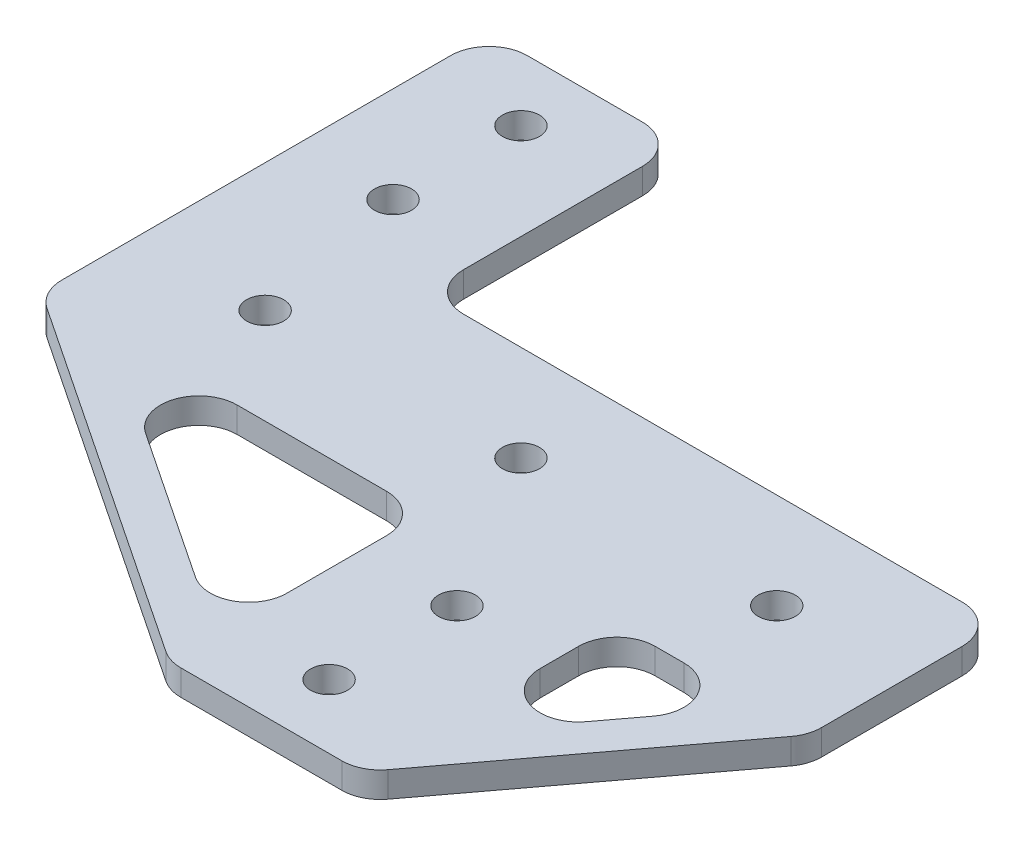
SolidWorks part; units mm, degrees
material "Thornel Mat VMA"
ref_plane "前视基准面" through (0, 0, 0) normal (0, 0, 1) x (1, 0, 0)
ref_plane "上视基准面" through (0, 0, 0) normal (0, 1, 0) x (1, 0, 0)
ref_plane "右视基准面" through (0, 0, 0) normal (1, 0, 0) x (0, 0, -1)
other "Configuration Table"
sketch "草图1" plane through (0, 0, 0) normal (0, 1, 0) x (1, 0, 0)
  line L0 (15, 35) -> (15, 15) construction
  line L1 (0, 0) -> (15, 0) construction
  line L2 (0, 0) -> (0, 35) construction
  line L3 (0, 35) -> (15, 35) construction
  line L4 (15, 0) -> (15, 35) construction
  line L5 (0, 0) -> (60, 0) construction
  line L6 (0, 0) -> (0, 15)
  line L7 (0, 15) -> (60, 15) construction
  line L8 (60, 0) -> (60, 15) construction
  line L9 (30, 15) -> (45, 15) construction
  line L10 (30, 15) -> (30, -20) construction
  line L11 (30, -20) -> (45, -20) construction
  line L12 (45, 15) -> (45, -20) construction
  line L13 (15, 15) -> (30, 15) construction
  line L14 (45, 15) -> (60, 15) construction
  line L15 (15, 0) -> (30, 0) construction
  line L16 (30, 0) -> (30, -20) construction
  line L17 (45, -20) -> (45, 0) construction
  line L18 (45, 0) -> (60, 0) construction
  line L19 (0, 0) -> (30, -20) construction
  line L20 (15, 35) -> (60, 15) construction
  line L21 (60, 0) -> (45, -20) construction
  line L22 (5.4083, 0) -> (30, 0)
  line L23 (30, 0) -> (30, -16.3944)
  line L24 (30, -16.3944) -> (5.4083, 0)
  line L25 (15, 28.8238) -> (15, 15) construction
  line L26 (15, 15) -> (52.6134, 15) construction
  line L28 (56.25, 0) -> (45, -15)
  line L29 (45, -15) -> (45, 0)
  line L30 (45, 0) -> (56.25, 0)
  line L31 (0, 0) -> (30, -20)
  line L32 (30, -20) -> (45, -20)
  line L33 (45, -20) -> (60, 0)
  line L34 (60, 0) -> (60, 15)
  line L35 (60, 15) -> (15, 35) construction
  line L36 (15, 35) -> (0, 35)
  line L37 (0, 35) -> (0, 0)
  line L38 (7.5, 46.7802) -> (7.5, -14.9998) construction
  line L39 (37.5, 36.5055) -> (37.5, -31.8877) construction
  line L40 (-7.4455, 7.5) -> (81.0629, 7.5) construction
  line L43 (26.7502, 15) -> (15, 15)
  line L44 (15, 15) -> (15, 28.8238)
  line L45 (45, 15) -> (60, 15)
  line L46 (15, 28.8238) -> (26.7502, 15)
  line L47 (15, 35) -> (32, 15)
  line L48 (32, 15) -> (45, 15)
  circle A1 centre (10, 7.5) radius 1.45
  circle A2 centre (30, 7.5) radius 1.45
  circle A3 centre (50, 7.5) radius 1.45
  circle A4 centre (7.5, 20) radius 1.45
  circle A5 centre (7.5, 30) radius 1.45
  circle A6 centre (37.5, -5) radius 1.45
  circle A7 centre (37.5, -15) radius 1.45
  dimension "D7" = 2.9
  dimension "D9" = 5
  dimension "D10" = 10
  dimension "D11" = 5
  dimension "D13" = 10
  dimension "D15" = 20
  dimension "D16" = 20
  dimension "D8" = 10
  dimension "D17" = 2.9
  dimension "D18" = 5
  dimension "D1" = 30
  dimension "D2" = 15
  dimension "D3" = 15
  dimension "D4" = 15
  dimension "D5" = 3
  dimension "D6" = 4
  dimension "D12" = 5
  dimension "D14" = 8.55
  dimension "D19" = 3
  dimension "D20" = 17
extrude "凸台-拉伸1" add sketch "草图1" along normal blind 2 contours L48 L47 L36 L37 L6 L31 L32 L33 L34 L45 A7 A6 A5 A4 A3 A2 A1 L23 L24 L22 L29 L30 L28 L44 L46 L43
sketch "草图2" plane through (0, 2, 0) normal (0, 1, 0) x (1, 0, 0)
  line L0 (15, 35) -> (15, 15)
  line L1 (15, 15) -> (32, 15)
  line L2 (32, 15) -> (15, 35)
extrude "切除-拉伸1" cut sketch "草图2" against normal through all
fillet "圆角1" radius 3 14 edges at (45, 1, 20) (30, 1, 20) (0, 1, 0) (0, 1, -35) (60, 1, 0) (30, 1, 0) (5.4083, 1, 0) (30, 1, 16.3944) (45, 1, 15) (56.25, 1, 0) (45, 1, 0) (60, 1, -15) (15, 1, -15) (15, 1, -35)
